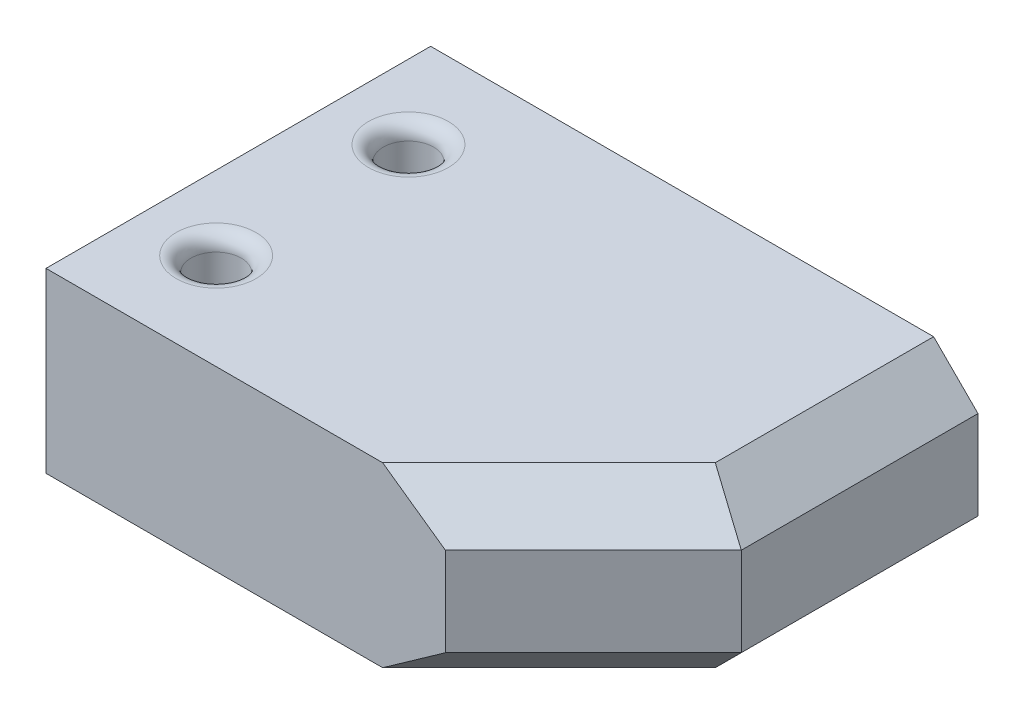
SolidWorks part; units mm, degrees
ref_plane "Front Plane" through (0, 0, 0) normal (0, 0, 1) x (1, 0, 0)
ref_plane "Top Plane" through (0, 0, 0) normal (0, 1, 0) x (1, 0, 0)
ref_plane "Right Plane" through (0, 0, 0) normal (1, 0, 0) x (0, 0, -1)
sketch "Sketch1" plane through (0, 0, 0) normal (0, 1, 0) x (1, 0, 0)
  line L0 (0, -6.5) -> (0, 6.5)
  line L1 (0, 6.5) -> (18.5, 6.5)
  line L2 (18.5, 6.5) -> (18.5, -6.5)
  line L3 (18.5, -6.5) -> (0, -6.5)
  point P4 (0, 0)
  dimension "D1" = 18.5
  dimension "D2" = 13
extrude "Boss-Extrude1" add sketch "Sketch1" along normal blind 6
sketch "Sketch2" plane through (0, 6, 0) normal (0, 1, 0) x (1, 0, 0)
  line L0 (2.5, 6.5) -> (2.5, -6.5) construction
  line L1 (18.5, 6.5) -> (0, 6.5) construction
  line L2 (0, -6.5) -> (18.5, -6.5) construction
  line L3 (5, 6.5) -> (5, -6.5) construction
  line L4 (0, 6.5) -> (0, -6.5) construction
  line L5 (0, 6.5) -> (5, 0) construction
  line L6 (5, 0) -> (0, -6.5) construction
  circle A0 centre (2.5, 3.25) radius 0.85
  circle A1 centre (2.5, -3.25) radius 0.85
  dimension "D3" = 1.7
  dimension "D4" = 1.7
  dimension "D1" = 2.5
  dimension "D2" = 2.5
extrude "Cut-Extrude1" cut sketch "Sketch2" against normal through all both and the other way through all
fillet "Fillet1" radius 0.5 4 edges at (2.5, 0, 4.1) (2.5, 0, -2.4) (2.5, 6, 2.4) (2.5, 6, -4.1)
chamfer "Chamfer1" distance 5 angle 45 1 edges at (18.5, 3, 6.5)
chamfer "Chamfer2" distance 1.5 angle 45 4 edges at (18.5, 0, -2.5) (16, 0, 4) (18.5, 6, -2.5) (16, 6, 4)
